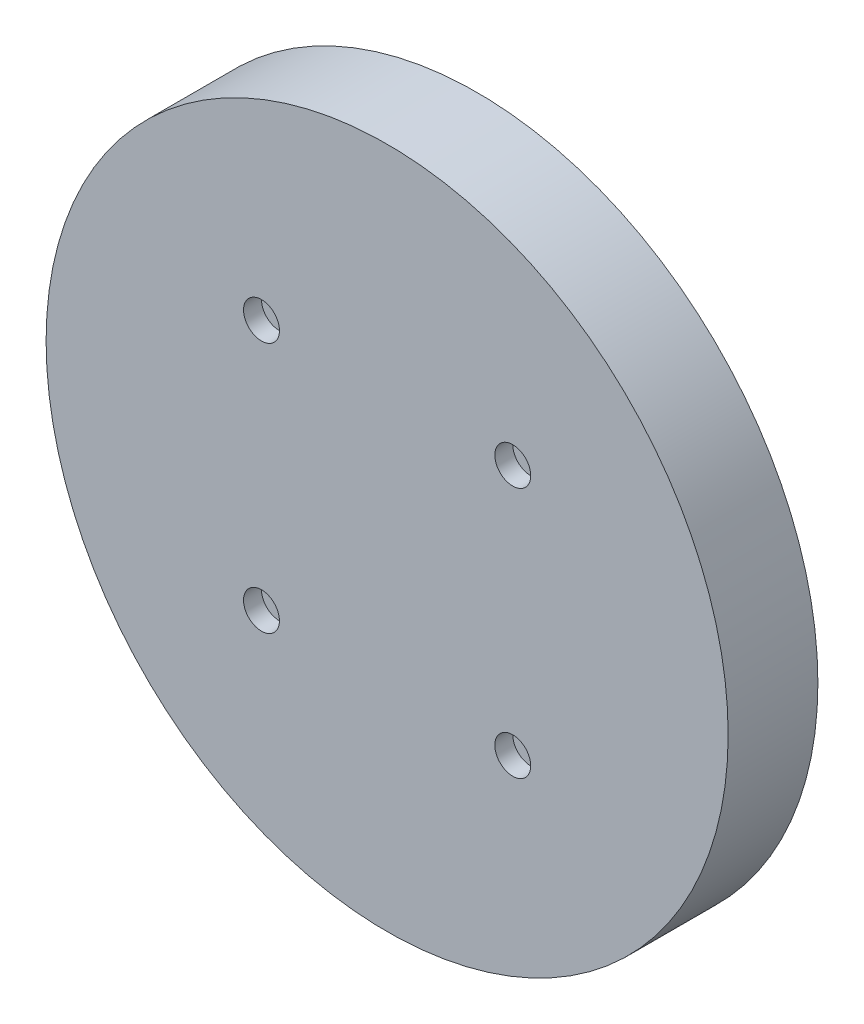
SolidWorks part; units mm, degrees
ref_plane "Front Plane" through (0, 0, 0) normal (0, 0, 1) x (1, 0, 0)
ref_plane "Top Plane" through (0, 0, 0) normal (0, 1, 0) x (1, 0, 0)
ref_plane "Right Plane" through (0, 0, 0) normal (1, 0, 0) x (0, 0, -1)
sketch "Sketch1" plane through (0, 0, 0) normal (0, 0, 1) x (1, 0, 0)
  line L0 (-26.9114, 0) -> (24.4081, 0) construction
  line L1 (0, -25.3468) -> (0, 24.721) construction
  circle A0 centre (0, 0) radius 19
  dimension "D1" = 38
extrude "Boss-Extrude1" add sketch "Sketch1" along normal blind 5
sketch "Sketch2" plane through (0, 0, 5) normal (0, 0, 1) x (1, 0, 0)
  line L0 (-23.611, 0) -> (23.4453, 0) construction
  line L1 (0, -20.7528) -> (0, 22.6436) construction
  circle A0 centre (-7, 7) radius 1
  circle A1 centre (7, 7) radius 1
  circle A2 centre (7, -7) radius 1
  circle A3 centre (-7, -7) radius 1
  dimension "D1" = 2
  dimension "D2" = 7
  dimension "D3" = 7
extrude "Cut-Extrude1" cut sketch "Sketch2" against normal blind 1
